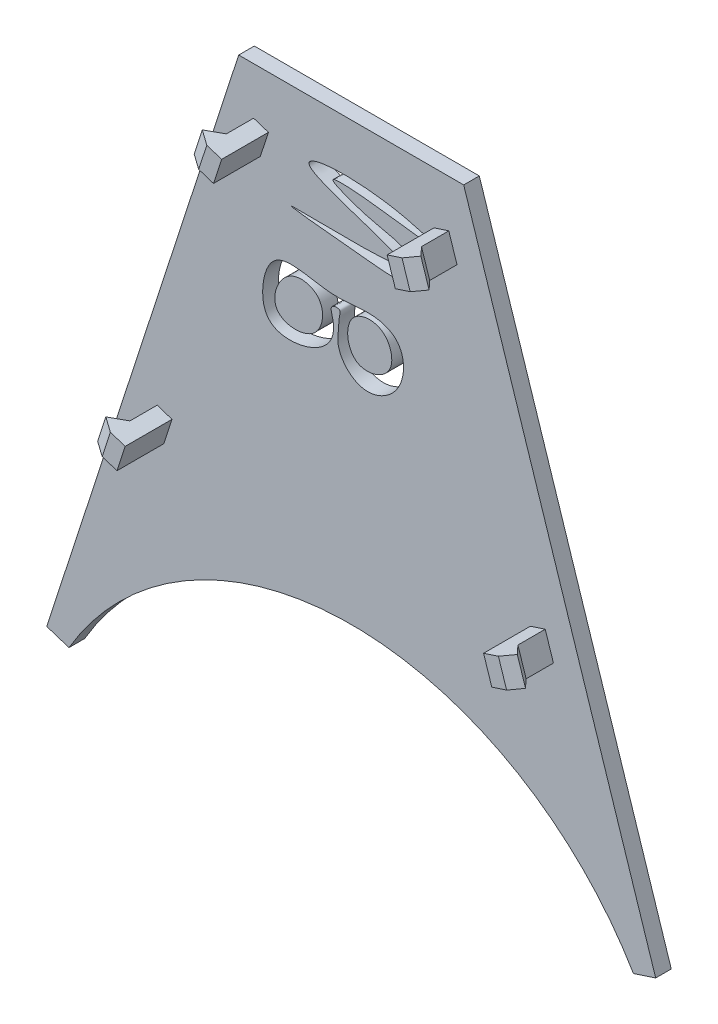
SolidWorks part; units mm, degrees
ref_plane "前视基准面" through (0, 0, 0) normal (0, 0, 1) x (1, 0, 0)
ref_plane "上视基准面" through (0, 0, 0) normal (0, 1, 0) x (1, 0, 0)
ref_plane "右视基准面" through (0, 0, 0) normal (1, 0, 0) x (0, 0, -1)
sketch "草图1" plane through (0, 0, 0) normal (0, 0, 1) x (1, 0, 0)
  line L0 (-39.0304, 22.2627) -> (-36.1773, 21.3356)
  line L1 (-39.0304, 22.2627) -> (-14.42, 98)
  line L2 (-14.42, 98) -> (14.42, 98)
  line L3 (14.42, 98) -> (39.0304, 22.2627)
  line L4 (39.0304, 22.2627) -> (36.1773, 21.3356)
  arc A0 (36.1773, 21.3356) -> (-36.1773, 21.3356) centre (0, 0) ccw
  point P6 (0, 98)
  dimension "D4" = 28.84
  dimension "D8" = 42
  dimension "D2" = 90
  dimension "D3" = 90
  dimension "D5" = 3
  dimension "D6" = 3
  dimension "D7" = 98
extrude "凸台-拉伸1" add sketch "草图1" along normal blind 2 contours L1 L2 L3 L4 A0 L0
sketch "草图2" plane through (0, 0, 2) normal (0, 0, 1) x (1, 0, 0)
  line L0 (-12.51, 91.9441) -> (-25.9222, 50.6685)
  line L1 (-25.9222, 50.6685) -> (-24.0201, 50.0504)
  line L2 (-24.0201, 50.0504) -> (-10.6079, 91.326)
  line L3 (-10.6079, 91.326) -> (-12.51, 91.9441)
  line L4 (0, 98) -> (0, 0) construction
  line L5 (-14.42, 98) -> (14.42, 98) construction
  line L6 (25.9222, 50.6685) -> (24.0201, 50.0504)
  line L7 (24.0201, 50.0504) -> (10.6079, 91.326)
  line L8 (12.51, 91.9441) -> (25.9222, 50.6685)
  line L9 (10.6079, 91.326) -> (12.51, 91.9441)
  line L10 (-39.0304, 22.2627) -> (-14.42, 98) construction
  dimension "D1" = 6.35
  dimension "D2" = 2
  dimension "D3" = 43.4
extrude "凸台-拉伸2" add sketch "草图2" along normal blind 6
sketch "草图3" plane through (-38.3386, 12.4579, 0) normal (-0.951, 0.309, 0) x (0, 0, 1)
  line L0 (2, 83.5773) -> (5.5, 83.5773)
  line L1 (8, 83.5773) -> (2, 83.5773) construction
  line L2 (5.5, 83.5773) -> (5.5, 40.1773)
  line L3 (8, 40.1773) -> (2, 40.1773) construction
  line L4 (5.5, 40.1773) -> (2, 40.1773)
sketch "草图4" plane through (25.8286, 79.4862, 0) normal (0.309, 0.951, 0) x (0.951, -0.309, 0)
  line L0 (-40.3118, -5.4877) -> (-41.8914, -7.0759)
  line L1 (-40.3118, -8) -> (-40.3118, -2) construction
  line L2 (-41.8914, -7.0759) -> (-40.3118, -8)
  line L3 (-40.3118, -5.4877) -> (-40.3118, -8)
  dimension "D1" = 1.83
  dimension "D2" = 2.24
extrude "凸台-拉伸3" add sketch "草图4" against normal up to vertex (43.4 mm away) up to point (-25.9222, 50.6685, 8)
sketch "草图5" plane through (-25.8286, 79.4862, 0) normal (-0.309, 0.951, 0) x (0.951, 0.309, 0)
  line L0 (40.3118, -8) -> (41.8959, -7.0837)
  line L1 (41.8959, -7.0837) -> (40.3118, -5.5)
  line L2 (40.3118, -8) -> (40.3118, -2) construction
  line L3 (40.3118, -5.5) -> (40.3118, -8)
  line L4 (16.5716, -2) -> (43.9999, -2) construction
  dimension "D1" = 2.24
  dimension "D2" = 1.83
  dimension "D3" = 3.5
extrude "凸台-拉伸4" add sketch "草图5" against normal up to surface (43.4 mm away) up to face at (24.9712, 50.3595, 5)
sketch "草图6" plane through (-38.3386, 12.4579, 0) normal (-0.951, 0.309, 0) x (0, 0, 1)
  line L0 (2, 40.1773) -> (2, 43.5773)
  line L1 (2, 83.5773) -> (2, 40.1773) construction
  line L2 (2, 83.5773) -> (2, 80.1773)
  dimension "D1" = 3.4
  dimension "D2" = 3.4
sketch "草图7" plane through (0, 0, 2) normal (0, 0, 1) x (1, 0, 0)
  line L0 (-13.5493, 88.7141) -> (-11.6565, 88.0991)
  line L1 (-24.0201, 50.0504) -> (-10.6079, 91.326) construction
  line L3 (-24.8715, 53.9021) -> (-22.9694, 53.284)
  line L4 (-22.9694, 53.284) -> (-11.6565, 88.0991)
  line L5 (-13.5493, 88.7141) -> (-24.8715, 53.9021)
  line L6 (0, 98) -> (0, 42) construction
  line L7 (-14.42, 98) -> (14.42, 98) construction
  line L8 (13.5493, 88.7141) -> (24.8715, 53.9021)
  line L9 (22.9694, 53.284) -> (11.6565, 88.0991)
  line L10 (24.8715, 53.9021) -> (22.9694, 53.284)
  line L11 (13.5493, 88.7141) -> (11.6565, 88.0991)
  arc A0 (36.1773, 21.3356) -> (-36.1773, 21.3356) centre (0, 0) ccw construction
sketch "草图8" plane through (-36.4365, 11.8398, 0) normal (0.951, -0.309, 0) x (0, 0, -1)
  line L0 (-2, 43.5773) -> (-8, 43.5773)
  line L1 (-8, 40.1773) -> (-8, 83.5773) construction
  line L2 (-2.8185, 80.2126) -> (-2, 80.2126)
  line L3 (-2, 40.1773) -> (-2, 83.5773) construction
  line L4 (-2, 80.2126) -> (-2, 43.5773)
  line L5 (-2.8185, 80.2126) -> (-8, 80.2126)
  line L6 (-8, 80.2126) -> (-8, 43.5773)
extrude "切除-拉伸3" cut sketch "草图8" against normal blind 43
sketch "草图9" plane through (36.4365, 11.8398, 0) normal (-0.951, -0.309, 0) x (0, 0, 1)
  line L1 (2, 83.5773) -> (2, 40.1773) construction
  line L3 (2, 80.1773) -> (8, 80.1773)
  line L4 (8, 83.5773) -> (8, 40.1773) construction
  line L5 (8, 80.1773) -> (8, 43.5773)
  line L6 (8, 43.5773) -> (2, 43.5773)
  line L7 (2, 43.5773) -> (2, 80.1773)
extrude "切除-拉伸4" cut sketch "草图9" against normal blind 43
sketch "草图10" plane through (0, 0, 0) normal (0, 0, -1) x (-1, 0, 0)
  spline S0 degree 3 poles (-12.5354, 88.9578) (-2.7632, 92.2923) (14.0527, 91.0002) (-18.9743, 83.4104) (14.4293, 85.2) (1.598, 83.8351) (-2.2309, 83.4742) (-8.9913, 82.8219) (-8.4546, 86.3981) (-6.0331, 87.5186) (-3.097, 88.0504) (-0.4875, 88.7788) (4.7963, 90.8586) (-4.7379, 89.927) (-7.2593, 89.4308) (-12.5354, 88.9578) (-2.7632, 92.2923) (14.0527, 91.0002) knots -0.129384 -0.072052 -0.047304 0 0.143751 0.291636 0.456176 0.517604 0.580122 0.648203 0.661792 0.691326 0.732233 0.765974 0.798028 0.870616 0.927948 0.952696 1 1.143751 1.291636 1.456176 only from (-7.0799, 90.5764) to (-7.0799, 90.5764)
  spline S1 degree 3 poles (2.4645, 76.5819) (9.8024, 79.4977) (11.6306, 74.0443) (10.8243, 68.6103) (3.0078, 69.9148) (1.9518, 73.9086) (2.87, 76.2608) (1.1913, 76.3331) (1.6406, 75.1191) (1.5562, 74.0564) (2.0529, 71.5523) (-1.2193, 67.6013) (-7.0705, 70.6607) (-6.9218, 76.2665) (-2.4965, 78.2097) (2.4645, 76.5819) (9.8024, 79.4977) (11.6306, 74.0443) knots -0.286997 -0.250603 -0.13555 0 0.073374 0.131989 0.267968 0.331163 0.354135 0.371123 0.384937 0.408066 0.434694 0.520231 0.617221 0.713003 0.749397 0.86445 1 1.073374 1.131989 1.267968 only from (9.8197, 77.4731) to (9.8197, 77.4731)
  spline S2 degree 3 poles (0.3262, 70.027) (1.0948, 76.8812) (-4.675, 77.5055) (-6.0831, 71.9076) (0.3262, 70.027) (1.0948, 76.8812) (-4.675, 77.5055) knots -0.77661 -0.534635 -0.279404 0 0.22339 0.465365 0.720596 1 1.22339 1.465365 1.720596 only from (-0.2087, 76.1139) to (-0.2087, 76.1139)
  spline S3 degree 3 poles (11.3193, 71.0293) (8.6107, 77.9116) (3.0897, 76.654) (3.8789, 70.7531) (11.3193, 71.0293) (8.6107, 77.9116) (3.0897, 76.654) knots -0.798667 -0.558691 -0.290817 0 0.201333 0.441309 0.709183 1 1.201333 1.441309 1.709183 only from (7.6083, 76.8706) to (7.6083, 76.8706)
  point P14 (1.6146, 74.0956)
extrude "切除-拉伸5" cut sketch "草图10" against normal blind 43
